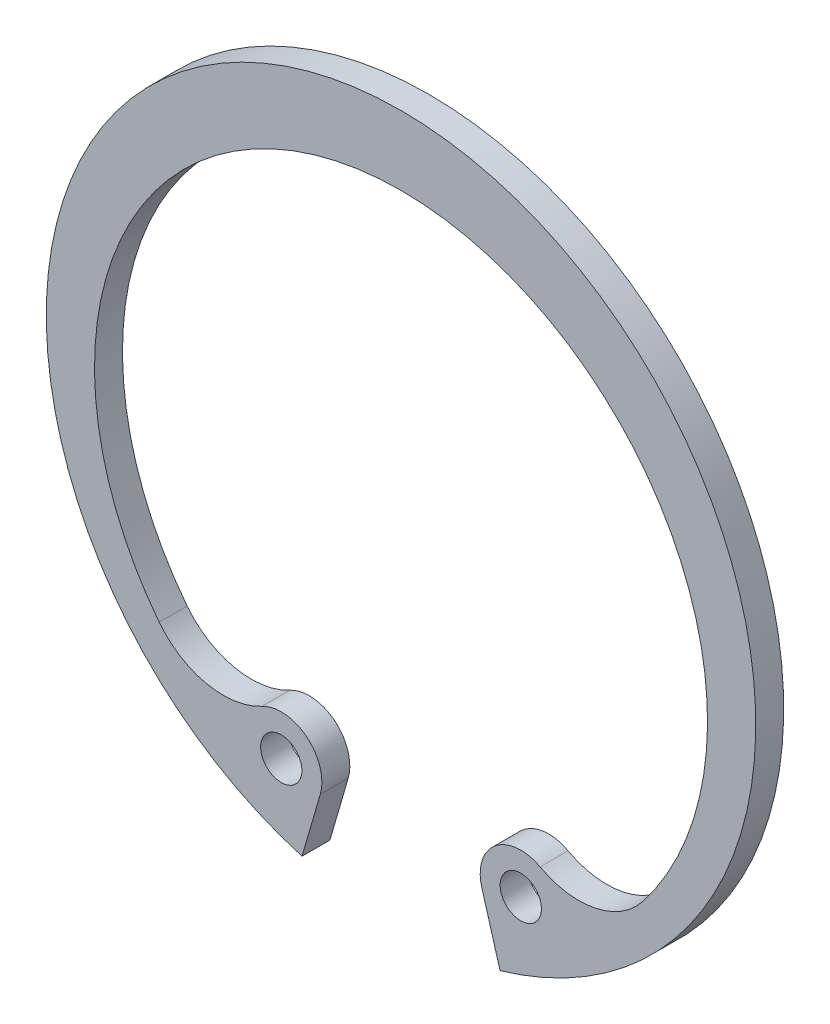
SolidWorks part; units mm, degrees
extrude "Body" add sketch "BodySke" against normal blind 1.0668
sketch "BodySke" plane through (0, 0, 0) normal (0, 0, 1) x (1, 0, 0)
  line L0 (-1.5431, 0) -> (1.5431, 0) construction
  line L1 (0, 0) -> (0, 10.8966) construction
  line L2 (3.7793, -13) -> (3.0826, -10.6034)
  line L3 (-3.7793, -13) -> (-3.0826, -10.6034)
  line L4 (0, 0) -> (10.0793, -9.0383) construction
  line L5 (0, 0) -> (-10.0793, -9.0383) construction
  line L6 (-4.3506, -9.4148) -> (-4.7902, -10.927) construction
  line L7 (4.3609, -9.4501) -> (4.78, -10.8916) construction
  arc A0 (-3.0826, -10.6034) -> (-5.3085, -8.8086) centre (-4.5704, -10.1709) ccw
  arc A1 (5.3085, -8.8086) -> (3.0826, -10.6034) centre (4.5704, -10.1709) ccw
  arc A2 (9.0959, -8.1565) -> (-9.0959, -8.1565) centre (0, -0.8012) ccw construction
  arc A3 (3.7793, -13) -> (-3.7793, -13) centre (0, 0) ccw
  circle A4 centre (4.5704, -10.1709) radius 0.7874
  circle A5 centre (-4.5704, -10.1709) radius 0.7874
  arc A7 (9.2298, -7.9878) -> (-9.2298, -7.9878) centre (0, -0.8012) ccw
  arc A8 (-4.5704, -10.1709) -> (4.5704, -10.1709) centre (0, 0) ccw construction
  arc A9 (-9.2298, -7.9878) -> (-5.3085, -8.8086) centre (-6.7848, -6.084) ccw
  arc A10 (5.3085, -8.8086) -> (9.2298, -7.9878) centre (6.7848, -6.084) ccw
  dimension "HoleOffsetRad" = 8.6614
  dimension "TipRad" = 1.651
  dimension "HoleDia" = 1.5748
  dimension "FilletRad" = 3.302
  dimension "LargeRad" = 8.9916
  dimension "SmallRad" = 9.8298
  dimension "GapAngle" = 31.055
ref_plane "Plane1" through (0, 0, 0) normal (0, 0, 1) x (1, 0, 0)
ref_plane "Plane2" through (0, 0, 0) normal (0, 1, 0) x (1, 0, 0)
ref_plane "Plane3" through (0, 0, 0) normal (1, 0, 0) x (0, 0, -1)
sketch "Clipboard" plane through (0, 0, 0) normal (0, 0, 1) x (1, 0, 0)
  line L0 (0, 0) -> (2.6416, 0)
  line L1 (0, 0) -> (0, 1.3208)
  line L2 (0, 0) -> (0, -3.937)
  circle A0 centre (0, 0) radius 0.7874
  circle A1 centre (0, 0) radius 12.7
  dimension "HoleDia" = 1.5748
  dimension "LugSection" = 3.937
sketch "ModLugSke" plane through (0, 0, 0) normal (0, 0, 1) x (1, 0, 0)
  line L0 (3.7793, -13) -> (2.8917, -9.9469)
  line L1 (-3.7793, -13) -> (-2.8917, -9.9469)
  line L2 (8.0396, -5.2486) -> (11.3362, -7.4009) construction
  line L3 (-8.0396, -5.2486) -> (-11.3362, -7.4009) construction
  line L4 (-3.7793, -13) -> (-3.0826, -10.6034) construction
  line L5 (3.0826, -10.6034) -> (3.7793, -13) construction
  line L6 (0, 0) -> (0, -12.7358) construction
  line L7 (10.1413, -6.6208) -> (11.3362, -7.4009)
  line L8 (-11.3362, -7.4009) -> (-10.1413, -6.6208)
  arc A0 (3.7793, -13) -> (11.3362, -7.4009) centre (0, 0) ccw
  arc A1 (-5.9654, -7.5231) -> (-3.3714, -8.9898) centre (0, 0) ccw
  arc A2 (3.7793, -13) -> (-3.7793, -13) centre (0, 0) ccw construction
  arc A3 (5.3085, -8.8086) -> (3.0826, -10.6034) centre (4.5704, -10.1709) ccw construction
  arc A4 (-5.9654, -7.5231) -> (-6.8331, -7.4496) centre (-6.4546, -8.1401) ccw
  arc A5 (-10.1413, -6.6208) -> (-6.8331, -7.4496) centre (-8.0396, -5.2486) ccw
  arc A6 (9.2298, -7.9878) -> (-9.2298, -7.9878) centre (0, -0.8012) ccw construction
  arc A7 (6.8331, -7.4496) -> (10.1413, -6.6208) centre (8.0396, -5.2486) ccw
  arc A8 (3.3714, -8.9898) -> (5.9654, -7.5231) centre (0, 0) ccw
  arc A9 (-11.3362, -7.4009) -> (-3.7793, -13) centre (0, 0) ccw
  circle A10 centre (-4.5704, -10.1709) radius 0.7874
  circle A11 centre (-4.5704, -10.1709) radius 0.7874 construction
  circle A12 centre (4.5704, -10.1709) radius 0.7874
  circle A13 centre (4.5704, -10.1709) radius 0.7874 construction
  arc A14 (-3.3714, -8.9898) -> (-2.8917, -9.9469) centre (-3.6478, -9.7271) cw
  arc A15 (3.3714, -8.9898) -> (2.8917, -9.9469) centre (3.6478, -9.7271) ccw
  arc A16 (5.9654, -7.5231) -> (6.8331, -7.4496) centre (6.4546, -8.1401) cw
  point P43 (2.6803, -9.2195)
extrude "ModLug" [suppressed] add sketch "ModLugSke" against normal through all
equation "' \"BoreDia@Clipboard\" = 0.25"
equation "' \"Thickness@Body\" = 0.015"
equation "' \"GrooveDia@BodySke\" = 0.268"
equation "' \"LugSection@Clipboard\" = 0.065"
equation "' \"LargeSection@Clipboard\" = 0.025"
equation "' \"SmallSection@Clipboard\" = 0.015"
equation "' \"HoleDia@Clipboard\" = 0.031"
equation "' \"BoreDia@Clipboard\" = 1.0"
equation "' \"Thickness@Body\" = 0.042"
equation "' \"GrooveDia@BodySke\" = 1.066"
equation "' \"LugSection@Clipboard\" = 0.155"
equation "' \"LargeSection@Clipboard\" = 0.104"
equation "' \"SmallSection@Clipboard\" = 0.052"
equation "' \"HoleDia@Clipboard\" = 0.062"
equation "\"TipRad@BodySke\" = (\"LugSection@Clipboard\" - (\"GrooveDia@BodySke\" / 2  -  \"BoreDia@Clipboard\" / 2 ) ) / 2"
equation "\"HoleOffsetRad@BodySke\" = (\"GrooveDia@BodySke\" / 2) - \"LugSection@Clipboard\"  + \"TipRad@BodySke\""
equation "\"LargeRad@BodySke\" =  \"GrooveDia@BodySke\" / 2 -  \"LargeSection@Clipboard\""
equation "\"SmallRad@BodySke\" =  \"GrooveDia@BodySke\" / 2 -  \"SmallSection@Clipboard\""
equation "\"HoleDia@BodySke\" =  \"HoleDia@Clipboard\""
equation "\"FilletRad@BodySke\" = \"TipRad@BodySke\" * 2"
equation "\"GapAngle@BodySke\" = 360 - 0.97 * 360 * ( \"BoreDia@Clipboard\" /  \"GrooveDia@BodySke\")"
equation "\"LugAng@ModLugSke\" = \"GapAngle@BodySke\"  + 2.5 * 360 * (\"LugSection@Clipboard\" / (\"BoreDia@Clipboard\" * 3.1416))"
